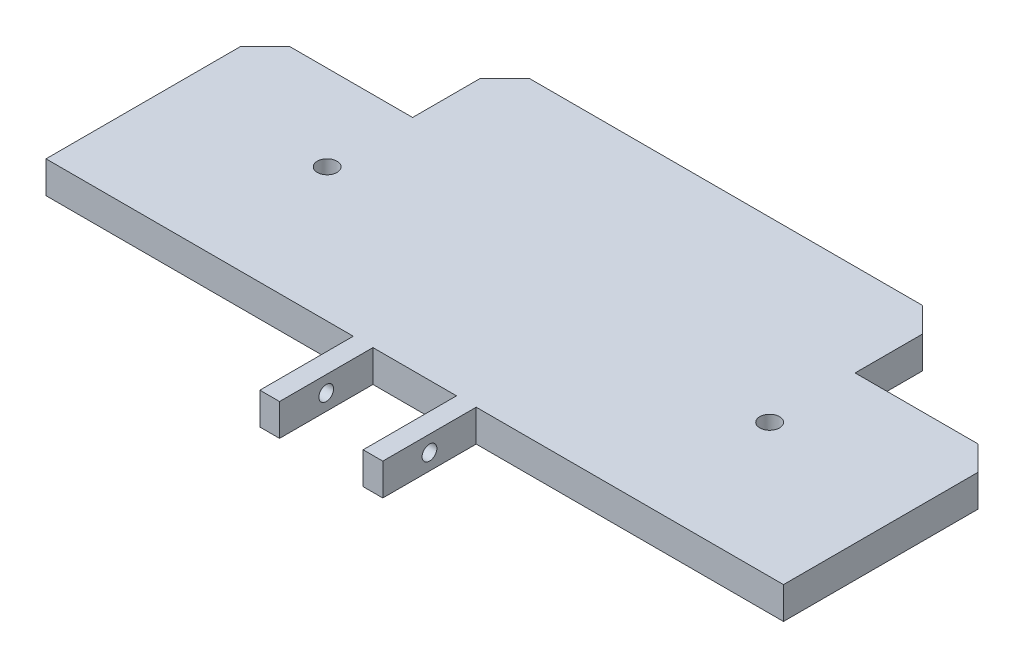
SolidWorks part; units mm, degrees
ref_plane "Front Plane" through (0, 0, 0) normal (0, 0, 1) x (1, 0, 0)
ref_plane "Top Plane" through (0, 0, 0) normal (0, 1, 0) x (1, 0, 0)
ref_plane "Right Plane" through (0, 0, 0) normal (1, 0, 0) x (0, 0, -1)
sketch "Sketch1" plane through (0, 0, 0) normal (0, 1, 0) x (1, 0, 0)
  line L1 (-75, 31.6575) -> (75, 31.6575)
  line L2 (-75, 31.6575) -> (-75, -31.6575)
  line L3 (-75, -31.6575) -> (75, -31.6575)
  line L4 (75, 31.6575) -> (75, -31.6575)
  line L5 (-75, 31.6575) -> (75, -31.6575) construction
  line L6 (-75, -31.6575) -> (75, 31.6575) construction
  point P0 (0, 0)
  dimension "D1" = 63.315
  dimension "D2" = 150
extrude "Boss-Extrude1" add sketch "Sketch1" along normal blind 6.5
sketch "Sketch2" plane through (0, 0, 31.6575) normal (0, 0, 1) x (1, 0, 0)
  line L0 (-8.5, 6.5) -> (-8.5, 0) construction
  line L1 (-75, 6.5) -> (75, 6.5) construction
  line L2 (-75, 0) -> (75, 0) construction
  line L3 (8.5, 0) -> (8.5, 6.5) construction
  line L5 (-8.5, 6.5) -> (-12.5, 6.5)
  line L6 (-8.5, 6.5) -> (-8.5, 0)
  line L7 (-8.5, 0) -> (-12.5, 0)
  line L8 (-12.5, 6.5) -> (-12.5, 0)
  line L9 (8.5, 6.5) -> (12.5, 6.5)
  line L10 (8.5, 6.5) -> (8.5, 0)
  line L11 (8.5, 0) -> (12.5, 0)
  line L12 (12.5, 6.5) -> (12.5, 0)
  dimension "D1" = 8.5
  dimension "D2" = 8.5
  dimension "D3" = 4
  dimension "D4" = 4
extrude "Boss-Extrude2" add sketch "Sketch2" along normal blind 19
sketch "Sketch3" plane through (0, 0, -31.6575) normal (0, 0, -1) x (-1, 0, 0)
  line L0 (-75, 0) -> (75, 0) construction
  line L1 (-75, 6.5) -> (-45, 6.5)
  line L2 (-75, 6.5) -> (-75, 0)
  line L3 (-75, 0) -> (-45, 0)
  line L4 (-45, 6.5) -> (-45, 0)
  line L6 (75, 6.5) -> (45, 6.5)
  line L7 (75, 6.5) -> (75, 0)
  line L8 (75, 0) -> (45, 0)
  line L9 (45, 6.5) -> (45, 0)
  dimension "D1" = 30
  dimension "D2" = 30
extrude "Cut-Extrude1" cut sketch "Sketch3" against normal blind 18.75
chamfer "Chamfer1" distance 5 angle 45 4 edges at (75, 3.25, -12.9075) (45, 3.25, -31.6575) (-45, 3.25, -31.6575) (-75, 3.25, -12.9075)
sketch "Sketch5" plane through (0, 0, 0) normal (0, -1, 0) x (1, 0, 0)
  line L0 (75, 4.4725) -> (-75, 4.4725) construction
  line L1 (75, 31.6575) -> (75, -7.9075) construction
  line L2 (-75, -7.9075) -> (-75, 31.6575) construction
  line L3 (40, -31.6575) -> (-40, -31.6575) construction
  circle A0 centre (45, 4.4725) radius 5
  circle A1 centre (-45, 4.4725) radius 5
  dimension "D2" = 30
  dimension "D1" = 36.13
  dimension "D3" = 30
extrude "Boss-Extrude3" add sketch "Sketch5" along normal blind 17.5
fillet "Fillet1" radius 5 2 edges at (-45, 0, 9.4725) (45, 0, 9.4725)
sketch "Sketch6" plane through (0, -17.5, 0) normal (0, -1, 0) x (1, 0, 0)
  circle A0 centre (45, 4.4725) radius 3.5
extrude "Cut-Extrude2" cut sketch "Sketch6" against normal blind 17.5
sketch "Sketch7" plane through (0, -17.5, 0) normal (0, -1, 0) x (1, 0, 0)
  circle A0 centre (-45, 4.4725) radius 3.5
extrude "Cut-Extrude3" cut sketch "Sketch7" against normal blind 17.5
sketch "Sketch8" plane through (0, 0, 0) normal (0, -1, 0) x (1, 0, 0)
  circle A0 centre (45, 4.4725) radius 2
  circle A1 centre (-45, 4.4725) radius 2
extrude "Cut-Extrude4" cut sketch "Sketch8" against normal blind 6.5
sketch "Sketch9" plane through (-12.5, 0, 0) normal (-1, 0, 0) x (0, 0, 1)
  line L0 (33.7375, 6.5) -> (33.7375, 0) construction
  line L1 (50.6575, 6.5) -> (31.6575, 6.5) construction
  line L2 (50.6575, 0) -> (31.6575, 0) construction
  line L3 (31.6575, 6.5) -> (31.6575, 0) construction
  line L4 (48.5775, 6.5) -> (48.5775, 0) construction
  line L5 (50.6575, 6.5) -> (50.6575, 0) construction
  line L6 (33.7375, 3.25) -> (48.5775, 3.25) construction
  circle A0 centre (41.1575, 3.25) radius 1.5
  dimension "D1" = 2.08
  dimension "D2" = 2.08
extrude "Cut-Extrude5" cut sketch "Sketch9" against normal blind 25
